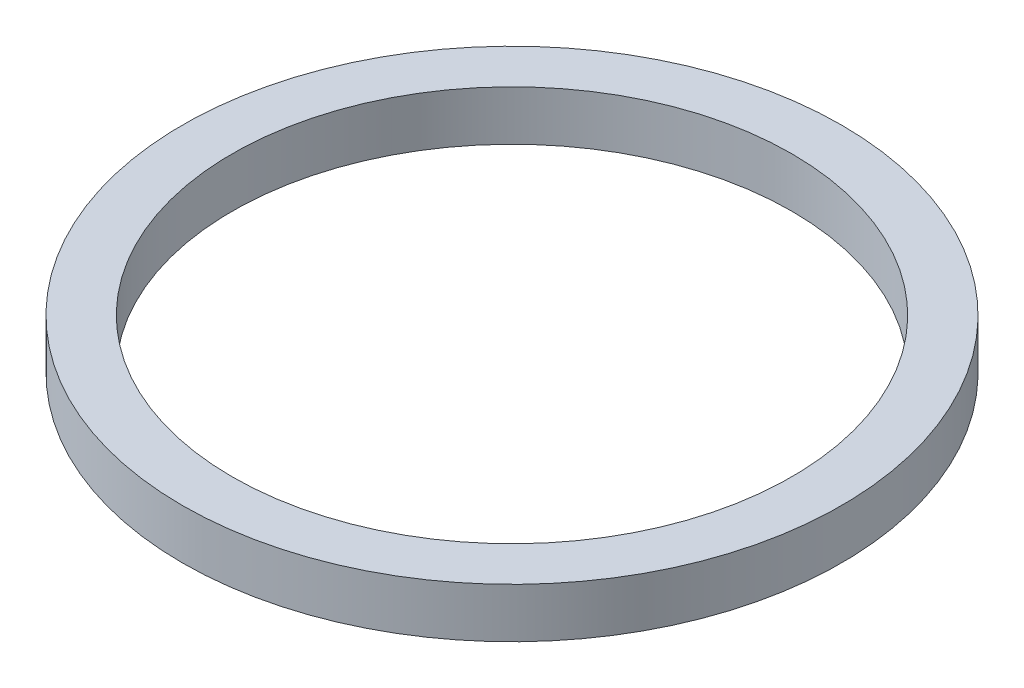
SolidWorks part; units mm, degrees
material "不锈钢 (铁素体)"
ref_plane "前视基准面" through (0, 0, 0) normal (0, 0, 1) x (1, 0, 0)
ref_plane "上视基准面" through (0, 0, 0) normal (0, 1, 0) x (1, 0, 0)
ref_plane "右视基准面" through (0, 0, 0) normal (1, 0, 0) x (0, 0, -1)
sketch "草图1" plane through (0, 0, 0) normal (0, 1, 0) x (1, 0, 0)
  circle A0 centre (0, 0) radius 45
  circle A1 centre (0, 0) radius 53
  dimension "D1" = 90
  dimension "D2" = 106
extrude "凸台-拉伸1" add sketch "草图1" along normal blind 8
